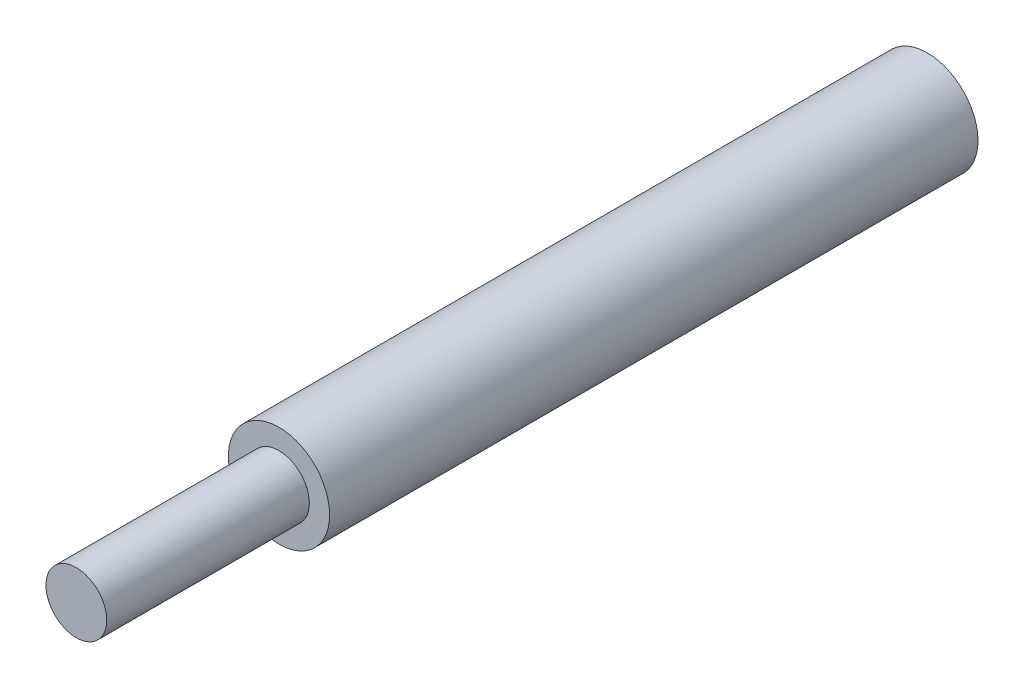
SolidWorks part; units mm, degrees
ref_plane "Front Plane" through (0, 0, 0) normal (0, 0, 1) x (1, 0, 0)
ref_plane "Top Plane" through (0, 0, 0) normal (0, 1, 0) x (1, 0, 0)
ref_plane "Right Plane" through (0, 0, 0) normal (1, 0, 0) x (0, 0, -1)
sketch "Sketch1" plane through (0, 0, 0) normal (0, 0, 1) x (1, 0, 0)
  circle A0 centre (0, 0) radius 12.5
  dimension "D1" = 25
extrude "Boss-Extrude1" add sketch "Sketch1" along normal mid plane 160
sketch "Sketch2" plane through (0, 0, 80) normal (0, 0, 1) x (1, 0, 0)
  circle A0 centre (0, 0) radius 7.5
  dimension "D1" = 15
extrude "Boss-Extrude2" add sketch "Sketch2" along normal blind 50
